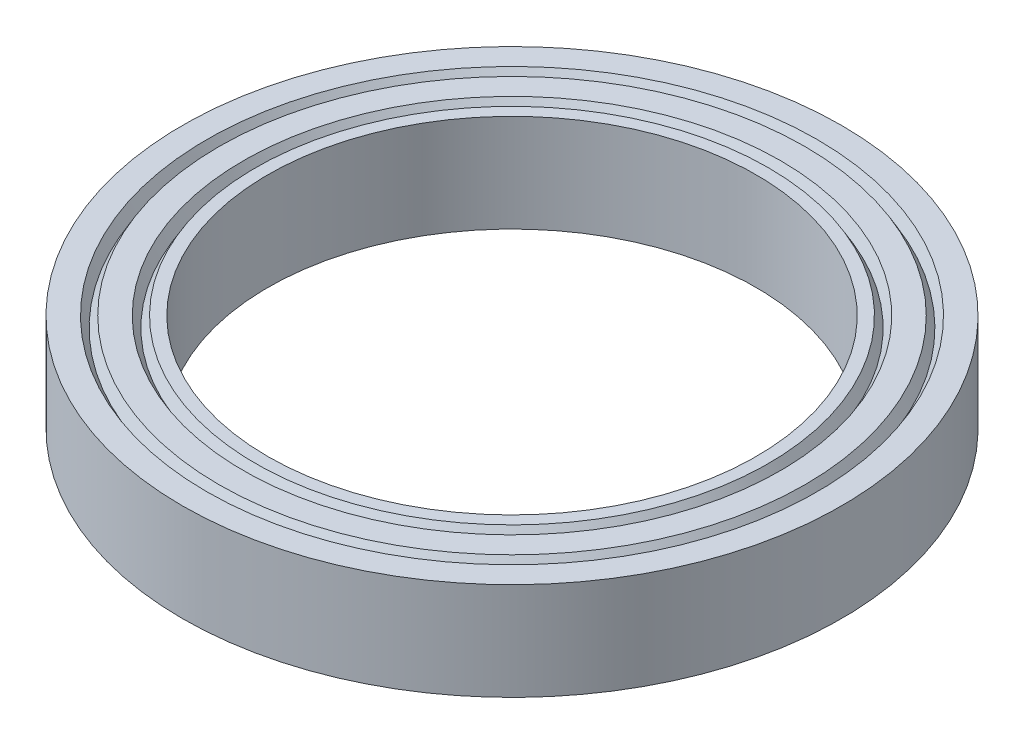
SolidWorks part; units mm, degrees
material "1023 碳钢板 (SS)"
ref_plane "前视基准面" through (0, 0, 0) normal (0, 0, 1) x (1, 0, 0)
ref_plane "上视基准面" through (0, 0, 0) normal (0, 1, 0) x (1, 0, 0)
ref_plane "右视基准面" through (0, 0, 0) normal (1, 0, 0) x (0, 0, -1)
sketch "草图1" plane through (0, 0, 0) normal (0, 1, 0) x (1, 0, 0)
  circle A0 centre (0, 0) radius 10
  circle A1 centre (0, 0) radius 13.5
  dimension "D1" = 20
  dimension "D2" = 27
extrude "凸台-拉伸1" add sketch "草图1" along normal blind 4
sketch "草图2" plane through (0, 4, 0) normal (0, 1, 0) x (1, 0, 0)
  line L0 (0, 0) -> (13.5, 0)
  circle A0 centre (0, 0) radius 13.5 construction
ref_plane "基准面1" through (0, 0, 0) normal (0, 0, 1) x (1, 0, 0)
sketch "草图3" plane through (0, 0, 0) normal (0, 0, 1) x (1, 0, 0)
  line L0 (-12.5, 4) -> (-12.25, 3.567)
  line L1 (13.5, 4) -> (-13.5, 4) construction
  line L2 (-12.25, 3.567) -> (-12, 4)
  line L3 (-12, 4) -> (-12.5, 4)
  line L4 (-11, 4) -> (-10.75, 3.567)
  line L5 (10, 4) -> (-10, 4) construction
  line L6 (-10.75, 3.567) -> (-10.5, 4)
  line L7 (-10.5, 4) -> (-11, 4)
  line L8 (0, 4) -> (0, 10.7684)
  dimension "D1" = 60
  dimension "D2" = 60
  dimension "D3" = 60
  dimension "D4" = 1
  dimension "D5" = 0.5
  dimension "D6" = 0.5
  dimension "D7" = 10.5
revolve "切除-旋转1" cut sketch "草图3" angle 360 about L8
ref_plane "基准面2" through (0, 2, 0) normal (0, 1, 0) x (1, 0, 0)
mirror "镜向1" about plane through (0, 2, 0) normal (0, 1, 0) of "切除-旋转1"
